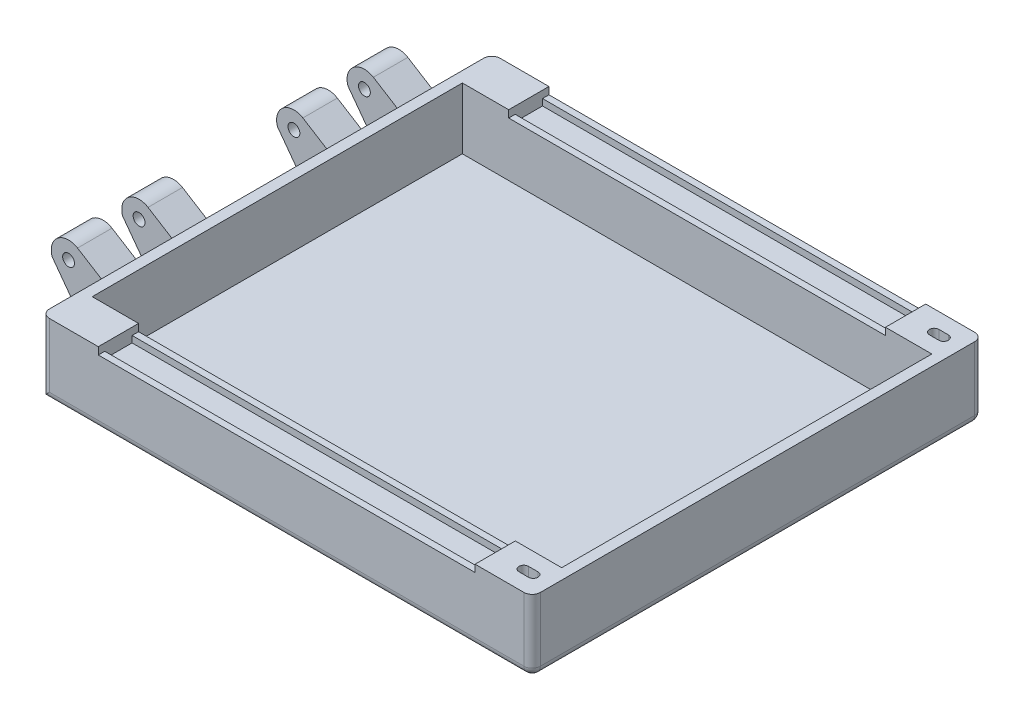
SolidWorks part; units mm, degrees
ref_plane "Front Plane" through (0, 0, 0) normal (0, 0, 1) x (1, 0, 0)
ref_plane "Top Plane" through (0, 0, 0) normal (0, 1, 0) x (1, 0, 0)
ref_plane "Right Plane" through (0, 0, 0) normal (1, 0, 0) x (0, 0, -1)
sketch "Sketch1" plane through (0, 0, 0) normal (0, 1, 0) x (1, 0, 0)
  line L1 (-114.02, -104.66) -> (114.02, -104.66)
  line L2 (-114.02, -104.66) -> (-114.02, 104.66)
  line L3 (-114.02, 104.66) -> (114.02, 104.66)
  line L4 (114.02, -104.66) -> (114.02, 104.66)
  line L5 (-114.02, -104.66) -> (114.02, 104.66) construction
  line L6 (-114.02, 104.66) -> (114.02, -104.66) construction
  point P0 (0, 0)
  dimension "D1" = 228.04
  dimension "D2" = 209.32
extrude "Boss-Extrude1" add sketch "Sketch1" along normal blind 33.5
sketch "Sketch2" plane through (0, 33.5, 0) normal (0, 1, 0) x (1, 0, 0)
  line L1 (-109.02, -85.96) -> (109.02, -85.96)
  line L2 (-109.02, -85.96) -> (-109.02, 85.96)
  line L3 (-109.02, 85.96) -> (109.02, 85.96)
  line L4 (109.02, -85.96) -> (109.02, 85.96)
  line L5 (-109.02, -85.96) -> (109.02, 85.96) construction
  line L6 (-109.02, 85.96) -> (109.02, -85.96) construction
  point P0 (0, 0)
  dimension "D1" = 218.04
  dimension "D2" = 171.92
extrude "Cut-Extrude1" cut sketch "Sketch2" against normal blind 28.5
sketch "Sketch4" plane through (0, 33.5, 0) normal (0, 1, 0) x (1, 0, 0)
  line L0 (-109.02, -85.96) -> (109.02, -85.96) construction
  line L1 (-87.5, -85.96) -> (87.5, -85.96)
  line L2 (-87.5, -85.96) -> (-87.5, -104.66)
  line L3 (-87.5, -104.66) -> (87.5, -104.66)
  line L4 (87.5, -85.96) -> (87.5, -104.66)
  line L5 (-114.02, -104.66) -> (114.02, -104.66) construction
  point P4 (0, -85.96)
  dimension "D1" = 175
extrude "Cut-Extrude2" cut sketch "Sketch4" against normal blind 3.35
sketch "Sketch5" plane through (0, 30.15, 0) normal (0, 1, 0) x (1, 0, 0)
  line L1 (-87.5, -88.96) -> (87.5, -88.96)
  line L2 (-87.5, -88.96) -> (-87.5, -101.66)
  line L3 (-87.5, -101.66) -> (87.5, -101.66)
  line L4 (87.5, -88.96) -> (87.5, -101.66)
  line L5 (-87.5, -85.96) -> (-87.5, -104.66) construction
  point P4 (-87.5, -95.31)
  dimension "D1" = 12.7
  dimension "D2" = 175
extrude "Cut-Extrude3" cut sketch "Sketch5" against normal blind 3
sketch "Sketch6" plane through (0, 33.5, 0) normal (0, 1, 0) x (1, 0, 0)
  line L0 (109.02, 85.96) -> (-109.02, 85.96) construction
  line L1 (-87.5, 104.66) -> (87.5, 104.66)
  line L2 (-87.5, 104.66) -> (-87.5, 85.96)
  line L3 (-87.5, 85.96) -> (87.5, 85.96)
  line L4 (87.5, 104.66) -> (87.5, 85.96)
  point P4 (0, 85.96)
  dimension "D1" = 175
  dimension "D2" = 18.7
extrude "Cut-Extrude4" cut sketch "Sketch6" against normal blind 3.35
sketch "Sketch7" plane through (0, 30.15, 0) normal (0, 1, 0) x (1, 0, 0)
  line L0 (-87.5, 104.66) -> (-87.5, 85.96) construction
  line L1 (-87.5, 101.66) -> (87.5, 101.66)
  line L2 (-87.5, 101.66) -> (-87.5, 88.96)
  line L3 (-87.5, 88.96) -> (87.5, 88.96)
  line L4 (87.5, 101.66) -> (87.5, 88.96)
  point P4 (-87.5, 95.31)
  dimension "D1" = 12.7
  dimension "D2" = 175
extrude "Cut-Extrude5" cut sketch "Sketch7" against normal blind 3
ref_plane "Plane1" through (0, 0, -35.96) normal (0, 0, 1) x (1, 0, 0)
sketch "Sketch9" plane through (0, 0, -35.96) normal (0, 0, 1) x (1, 0, 0)
  line L0 (-114.02, 0) -> (-136.9054, 30.9801)
  line L4 (-114.02, 33.5) -> (-114.02, 0)
  line L5 (-114.02, 33.5) -> (-125.0955, 40.3891)
  arc A0 (-125.0955, 40.3891) -> (-136.9054, 30.9801) centre (-129.26, 33.5) ccw
  circle A1 centre (-129.26, 33.5) radius 2.75
  point P8 (-129.26, 33.5)
  point P9 (-125.0955, 40.3891)
  dimension "D2" = 16.1
  dimension "D3" = 5.5
  dimension "D1" = 15.24
extrude "Boss-Extrude2" add sketch "Sketch9" along normal blind 8 and the other way blind 8
ref_plane "Plane2" through (0, 0, -52.33) normal (0, 0, 1) x (1, 0, 0)
mirror "Mirror1" about plane through (0, 0, -52.33) normal (0, 0, 1) of "Boss-Extrude2"
ref_plane "Plane3" through (0, 0, 0) normal (0, 0, 1) x (1, 0, 0)
mirror "Mirror2" about plane through (0, 0, 0) normal (0, 0, 1) of "Mirror1", "Boss-Extrude2"
sketch "Sketch11" plane through (0, 33.5, 0) normal (0, 1, 0) x (1, 0, 0)
  line L0 (114.02, 104.66) -> (87.5, 104.66) construction
  line L1 (87.5, 85.96) -> (87.5, 104.66) construction
  line L4 (100.76, 93.11) -> (105.16, 93.11)
  line L6 (100.76, 97.51) -> (105.16, 97.51)
  arc A0 (100.76, 97.51) -> (100.76, 93.11) centre (100.76, 95.31) ccw
  arc A1 (105.16, 93.11) -> (105.16, 97.51) centre (105.16, 95.31) ccw
  point P1 (110.31, 95.31)
  point P4 (100.76, 104.66)
  point P7 (87.5, 95.31)
  dimension "D1" = 4.4
  dimension "D4" = 4.4
  dimension "D2" = 4.4
extrude "Cut-Extrude6" cut sketch "Sketch11" against normal blind 33.5
mirror "Mirror3" about plane through (0, 0, 0) normal (0, 0, 1) of "Cut-Extrude6"
fillet "Fillet3" radius 3.81 7 edges at (-114.02, 16.75, 104.66) (0, 0, 104.66) (114.02, 16.75, 104.66) (114.02, 0, 0) (114.02, 16.75, -104.66) (0, 0, -104.66) (-114.02, 16.75, -104.66)
